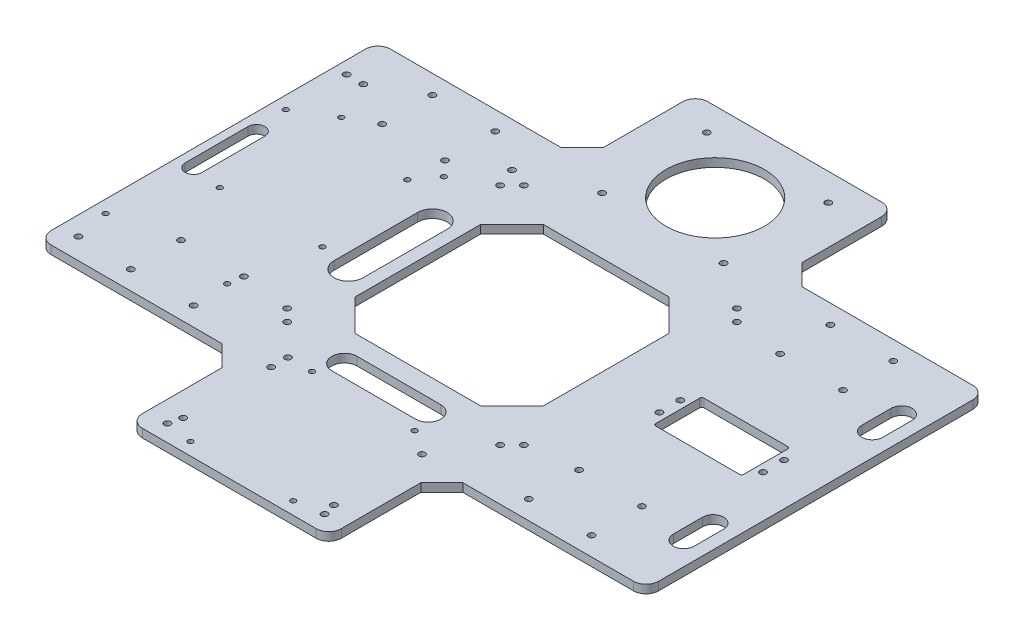
SolidWorks part; units mm, degrees
material "Thornel Mat VMA"
ref_plane "前视基准面" through (0, 0, 0) normal (0, 0, 1) x (1, 0, 0)
ref_plane "上视基准面" through (0, 0, 0) normal (0, 1, 0) x (1, 0, 0)
ref_plane "右视基准面" through (0, 0, 0) normal (1, 0, 0) x (0, 0, -1)
other "Configuration Table"
sketch "草图1" plane through (0, 0, 0) normal (0, 1, 0) x (1, 0, 0)
  line L0 (0, 0) -> (0, 135) construction
  line L1 (-145, -135) -> (145, -135)
  line L2 (-145, -135) -> (-145, 135)
  line L3 (-145, 135) -> (145, 135)
  line L4 (145, -135) -> (145, 135)
  line L5 (-145, -135) -> (145, 135) construction
  line L6 (-145, 135) -> (145, -135) construction
  line L7 (0, 0) -> (145, 0) construction
  line L8 (-47.5, 135) -> (-47.5, 81)
  line L9 (-47.5, 81) -> (-145, 81)
  line L10 (47.5, 81) -> (145, 81)
  line L11 (47.5, 135) -> (47.5, 81)
  line L12 (47.5, -81) -> (145, -81)
  line L13 (47.5, -135) -> (47.5, -81)
  line L14 (-47.5, -81) -> (-145, -81)
  line L15 (-47.5, -135) -> (-47.5, -81)
  point P0 (0, 0)
  dimension "D1" = 290
  dimension "D2" = 270
  dimension "D3" = 162
  dimension "D4" = 95
extrude "凸台-拉伸1" add sketch "草图1" along normal blind 4 contours L15 L1 L13 L12 L4 L10 L11 L3 L8 L9 L2 L14
sketch "草图2" plane through (0, 4, 0) normal (0, 1, 0) x (1, 0, 0)
  line L0 (0, 0) -> (145, 0) construction
  line L1 (145, -81) -> (145, 81) construction
  line L2 (0, 0) -> (0, 135) construction
  line L3 (-47.5, 135) -> (47.5, 135) construction
  line L4 (47.5, 81) -> (145, 81) construction
  circle A0 centre (110, 72) radius 1.5
  circle A1 centre (80, 72) radius 1.5
  circle A2 centre (80, 48) radius 1.5
  circle A3 centre (110, 48) radius 1.5
  circle A4 centre (110, -48) radius 1.5
  circle A5 centre (110, -72) radius 1.5
  circle A6 centre (80, -48) radius 1.5
  circle A7 centre (80, -72) radius 1.5
  circle A8 centre (-80, -72) radius 1.5
  circle A9 centre (-80, -48) radius 1.5
  circle A10 centre (-110, -72) radius 1.5
  circle A11 centre (-110, -48) radius 1.5
  circle A12 centre (-110, 48) radius 1.5
  circle A13 centre (-80, 48) radius 1.5
  circle A14 centre (-80, 72) radius 1.5
  circle A15 centre (-110, 72) radius 1.5
  dimension "D1" = 3
  dimension "D2" = 3
  dimension "D3" = 3
  dimension "D4" = 3
  dimension "D11" = 80
  dimension "D12" = 9
  dimension "D5" = 24
  dimension "D6" = 24
  dimension "D7" = 30
  dimension "D8" = 30
  dimension "D9" = 80
  dimension "D10" = 9
extrude "切除-拉伸1" cut sketch "草图2" against normal blind 4
sketch "草图3" plane through (0, 4, 0) normal (0, 1, 0) x (1, 0, 0)
  line L0 (0, 0) -> (0, 110.5115) construction
  line L1 (0, 0) -> (145, 0) construction
  line L2 (145, -81) -> (145, 81) construction
  line L3 (-86.4083, 97) -> (86.4083, 97) construction
  line L4 (0, 0) -> (0, 108.4938) construction
  line L7 (0, 0) -> (0, -114.288) construction
  circle A5 centre (0, 97) radius 23.5
  circle A33 centre (29, 122) radius 1.5
  circle A34 centre (29, 72) radius 1.5
  circle A35 centre (-29, 72) radius 1.5
  circle A36 centre (-29, 122) radius 1.5
  point P13 (0, 97)
  dimension "D2" = 97
  dimension "D6" = 47
  dimension "D12" = 25
  dimension "D8" = 3
  dimension "D5" = 0
  dimension "D9" = 29
extrude "切除-拉伸2" cut sketch "草图3" against normal blind 4
sketch "草图4" plane through (0, 4, 0) normal (0, 1, 0) x (1, 0, 0)
  line L1 (-45, -45) -> (45, -45)
  line L2 (-45, -45) -> (-45, 45)
  line L3 (-45, 45) -> (45, 45)
  line L4 (45, -45) -> (45, 45)
  line L5 (-45, -45) -> (45, 45) construction
  line L6 (-45, 45) -> (45, -45) construction
  point P0 (0, 0)
  dimension "D1" = 90
  dimension "D2" = 90
extrude "切除-拉伸3" cut sketch "草图4" against normal blind 4
fillet "圆角3" radius 6 8 edges at (-47.5, 2, -135) (47.5, 2, -135) (145, 2, -81) (145, 2, 81) (-47.5, 2, 135) (47.5, 2, 135) (-145, 2, 81) (-145, 2, -81)
chamfer "倒角1" distance 10 angle 45 4 edges at (47.5, 2, 81) (-47.5, 2, 81) (47.5, 2, -81) (-47.5, 2, -81)
sketch "草图7" plane through (0, 4, 0) normal (0, 1, 0) x (1, 0, 0)
  line L0 (0, 0) -> (0, 142.9478) construction
  line L1 (0, 0) -> (-184.5222, 0) construction
  line L2 (-137, -15) -> (-137, 15) construction
  line L5 (-58, -20) -> (-58, 20) construction
  line L6 (-65, -20) -> (-65, 20)
  line L7 (-51, -20) -> (-51, 20)
  line L8 (0, 0) -> (165.4514, 0) construction
  line L14 (-110, 0) -> (-110, 75.2826) construction
  line L15 (134, 38) -> (134, 52) construction
  line L33 (-141, -15) -> (-141, 15)
  line L34 (-133, -15) -> (-133, 15)
  line L35 (63, 0) -> (63, 55.2292) construction
  line L36 (0, -15) -> (172.3256, -15) construction
  line L38 (129, 38) -> (129, 52)
  line L39 (139, 38) -> (139, 52)
  line L40 (134, -38) -> (134, -52) construction
  line L41 (129, -38) -> (129, -52)
  line L42 (139, -38) -> (139, -52)
  arc A2 (-65, -20) -> (-51, -20) centre (-58, -20) ccw
  arc A3 (-51, 20) -> (-65, 20) centre (-58, 20) ccw
  arc A34 (-141, -15) -> (-133, -15) centre (-137, -15) ccw
  arc A35 (-133, 15) -> (-141, 15) centre (-137, 15) ccw
  arc A56 (129, 38) -> (139, 38) centre (134, 38) ccw
  arc A57 (139, 52) -> (129, 52) centre (134, 52) ccw
  arc A58 (129, -38) -> (139, -38) centre (134, -38) cw
  arc A59 (139, -52) -> (129, -52) centre (134, -52) cw
  point P6 (-137, 0)
  point P13 (-58, 0)
  point P21 (134, 45)
  point P37 (134, -45)
  dimension "D2" = 30
  dimension "D5" = 7
  dimension "D8" = 5
  dimension "D10" = 45
  dimension "D9" = 134
  dimension "D3" = 4
  dimension "D23" = 15
  dimension "D1" = 14
  dimension "D4" = 40
  dimension "D6" = 58
  dimension "D7" = 110
  dimension "D20" = 133
  dimension "D24" = 63
extrude "切除-拉伸6" cut sketch "草图7" against normal blind 4
chamfer "倒角2" distance 15 angle 45 4 edges at (45, 2, 45) (-45, 2, 45) (45, 2, -45) (-45, 2, -45)
sketch "草图8" plane through (0, 4, 0) normal (0, 1, 0) x (1, 0, 0)
  line L0 (0, 0) -> (0, 168.9929) construction
  line L1 (0, 0) -> (-169.1558, 0) construction
  line L2 (-103, 0) -> (-103, 65.828) construction
  line L3 (-103, -6) -> (-155.6162, -6) construction
  line L4 (0, 0) -> (-184.1789, 0) construction
  line L5 (0, 0) -> (0, 73.477) construction
  line L6 (-57.5, 81) -> (-139, 81) construction
  circle A15 centre (-139, 60) radius 1.5
  circle A16 centre (-131, 60) radius 1.5
  dimension "D2" = 8
  dimension "D4" = 103
  dimension "D5" = 6
  dimension "D6" = 0
  dimension "D7" = 3
  dimension "D8" = 3
  dimension "D11" = 28
  dimension "D12" = 36
  dimension "D10" = 21
extrude "切除-拉伸7" cut sketch "草图8" against normal blind 4
sketch "草图9" plane through (0, 4, 0) normal (0, 1, 0) x (1, 0, 0)
  line L0 (0, 0) -> (0, 165.3902) construction
  line L1 (0, 0) -> (179.4814, 0) construction
  line L2 (50.8431, 56.5) -> (56.5, 50.8431) construction
  line L3 (-62.5, -62.5) -> (62.5, -62.5) construction
  line L4 (-62.5, -62.5) -> (-62.5, 62.5) construction
  line L5 (-62.5, 62.5) -> (62.5, 62.5) construction
  line L6 (62.5, -62.5) -> (62.5, 62.5) construction
  line L7 (-62.5, -62.5) -> (62.5, 62.5) construction
  line L8 (-62.5, 62.5) -> (62.5, -62.5) construction
  line L18 (-50.3018, -50.3018) -> (40.4104, 40.4104) construction
  line L23 (-50.8431, -50.8431) -> (45.8431, 45.8431) construction
  line L24 (-48.3431, 48.3431) -> (48.3431, -48.3431) construction
  line L29 (-52.5221, -52.5221) -> (52.5221, 52.5221) construction
  line L30 (-52.5221, 52.5221) -> (52.5221, -52.5221) construction
  circle A0 centre (50.8431, 56.5) radius 1.5
  circle A1 centre (56.5, 50.8431) radius 1.5
  circle A2 centre (56.5, -50.8431) radius 1.5
  circle A3 centre (50.8431, -56.5) radius 1.5
  circle A4 centre (-50.8431, -56.5) radius 1.5
  circle A5 centre (-56.5, -50.8431) radius 1.5
  circle A6 centre (-56.5, 50.8431) radius 1.5
  circle A7 centre (-50.8431, 56.5) radius 1.5
  circle A8 centre (-37.5, -127) radius 1.5
  circle A9 centre (37.5, -127) radius 1.5
  dimension "D3" = 3
  dimension "D4" = 3
  dimension "D6" = 8
  dimension "D9" = 3
  dimension "D11" = 127
  dimension "D1" = 125
  dimension "D2" = 125
  dimension "D5" = 45
  dimension "D7" = 6
  dimension "D8" = 6
  dimension "D10" = 37.5
extrude "切除-拉伸8" cut sketch "草图9" against normal blind 4
sketch "草图10" plane through (0, 4, 0) normal (0, 1, 0) x (1, 0, 0)
  line L0 (0, 0) -> (173.0266, 0) construction
  line L1 (0, 0) -> (0, 114.2255) construction
sketch "草图11" plane through (0, 4, 0) normal (0, 1, 0) x (1, 0, 0)
  line L0 (0, 0) -> (183.5565, 0) construction
  line L1 (0, 0) -> (0, -155.5612) construction
sketch "草图12" plane through (0, 4, 0) normal (0, 1, 0) x (1, 0, 0)
  line L0 (-20, -60) -> (20, -60) construction
  line L1 (0, 0) -> (0, -155.5612) construction
  line L2 (-20, -54) -> (20, -54)
  line L3 (-20, -66) -> (20, -66)
  line L4 (0, 0) -> (173.0266, 0) construction
  arc A0 (-20, -54) -> (-20, -66) centre (-20, -60) ccw
  arc A1 (20, -66) -> (20, -54) centre (20, -60) ccw
  point P4 (0, -60)
  dimension "D2" = 6
  dimension "D1" = 40
  dimension "D3" = 60
extrude "切除-拉伸9" cut sketch "草图12" against normal blind 10
sketch "草图14" plane through (0, 4, 0) normal (0, 1, 0) x (1, 0, 0)
  line L0 (0, 0) -> (0, -145.4864) construction
  line L1 (0, 0) -> (173.1076, 0) construction
  line L2 (0, -100) -> (89.1596, -100) construction
  circle A0 centre (36, -79) radius 1.5
  circle A1 centre (36, -121) radius 1.5
  circle A2 centre (-36, -121) radius 1.5
  circle A3 centre (-36, -79) radius 1.5
  circle A4 centre (-24.5, -71) radius 1.25
  circle A5 centre (24.5, -71) radius 1.25
  circle A6 centre (24.5, -129) radius 1.25
  circle A7 centre (-24.5, -129) radius 1.25
  dimension "D1" = 3
  dimension "D2" = 42
  dimension "D3" = 72
  dimension "D5" = 2.5
  dimension "D6" = 49
  dimension "D7" = 58
  dimension "D4" = 100
extrude "切除-拉伸10" cut sketch "草图14" against normal blind 10
sketch "草图15" plane through (0, 4, 0) normal (0, 1, 0) x (1, 0, 0)
  line L0 (0, 0) -> (175.5609, 0) construction
  line L1 (0, 0) -> (0, 158.0719) construction
  line L2 (100.11, 0) -> (100.11, 39.6302) construction
  line L3 (79.11, -11.5) -> (121.11, -11.5)
  line L4 (79.11, -11.5) -> (79.11, 11.5)
  line L5 (79.11, 11.5) -> (121.11, 11.5)
  line L6 (121.11, -11.5) -> (121.11, 11.5)
  line L7 (79.11, -11.5) -> (121.11, 11.5) construction
  line L8 (79.11, 11.5) -> (121.11, -11.5) construction
  line L9 (110, 0) -> (110, 79.3701) construction
  circle A0 centre (75.36, 5) radius 1.5
  circle A2 centre (75.36, -5) radius 1.5
  circle A4 centre (124.86, -5) radius 1.5
  circle A5 centre (124.86, 5) radius 1.5
  point P3 (100.11, 0)
  dimension "D3" = 10
  dimension "D4" = 3
  dimension "D5" = 49.5
  dimension "D1" = 42
  dimension "D2" = 23
  dimension "D6" = 9.89
  dimension "D7" = 110
extrude "切除-拉伸11" cut sketch "草图15" against normal blind 10
fillet "圆角4" radius 1 4 edges at (79.11, 2, 11.5) (121.11, 2, 11.5) (121.11, 2, -11.5) (79.11, 2, -11.5)
sketch "草图16" plane through (0, 4, 0) normal (0, 1, 0) x (1, 0, 0)
  line L0 (0, 12) -> (-202.0071, 12) construction
  line L1 (0, 12) -> (0, 203.0309) construction
  line L2 (-98, -2.3134) -> (-98, 98.9217) construction
  line L4 (0, 0) -> (0, 12) construction
  line L5 (0, 0) -> (-183.682, 0) construction
  circle A0 centre (-73.5, 41) radius 1.25
  circle A1 centre (-122.5, 41) radius 1.25
  circle A2 centre (-73.5, -17) radius 1.25
  circle A3 centre (-122.5, -17) radius 1.25
  dimension "D1" = 58
  dimension "D2" = 49
  dimension "D3" = 2.5
  dimension "D4" = 98
  dimension "D5" = 12
extrude "切除-拉伸12" cut sketch "草图16" against normal blind 10
sketch "草图19" plane through (0, 4, 0) normal (0, 1, 0) x (1, 0, 0)
  line L0 (0, 0) -> (-178.7427, 0) construction
  line L1 (0, 0) -> (0, 171.7177) construction
  line L2 (-98, -10.9053) -> (-98, 46.7773) construction
  line L3 (-98, -7.4) -> (-15.7423, -7.4) construction
  circle A0 centre (-65, 50) radius 1.5
  circle A1 centre (-131, 50) radius 1.5
  circle A2 centre (-65, -64.8) radius 1.5
  circle A3 centre (-131, -64.8) radius 1.5
  dimension "D1" = 3
  dimension "D2" = 114.8
  dimension "D3" = 66
  dimension "D4" = 98
  dimension "D5" = 7.4
sketch "草图20" plane through (0, 4, 0) normal (0, 1, 0) x (1, 0, 0)
  line L0 (0, 0) -> (0, 140.7476) construction
  line L1 (0, 0) -> (-188.6657, 0) construction
  circle A0 centre (-60, 60) radius 1.5
  dimension "D1" = 3
  dimension "D2" = 60
  dimension "D3" = 60
sketch "草图22" plane through (0, 4, 0) normal (0, 1, 0) x (1, 0, 0)
  line L0 (0, 0) -> (154.1719, 0) construction
  line L1 (61, 0) -> (61, 40.4074) construction
  circle A0 centre (73, 13) radius 1.5
  circle A1 centre (49, 13) radius 1.5
  circle A2 centre (73, -13) radius 1.5
  circle A3 centre (49, -13) radius 1.5
  dimension "D1" = 24
  dimension "D2" = 26
  dimension "D3" = 3
  dimension "D4" = 61
sketch "草图23" plane through (0, 4, 0) normal (0, 1, 0) x (1, 0, 0)
  line L0 (0, 0) -> (-194.1261, 0) construction
  line L1 (-110, 0) -> (-110, 133.2192) construction
  line L3 (0, 0) -> (0, 84.0673) construction
  line L4 (0, -12) -> (-198.9065, -12) construction
  circle A0 centre (-81, 31) radius 1.25
  circle A3 centre (-139, 31) radius 1.25
  circle A4 centre (-81, -55) radius 1.25
  circle A5 centre (-139, -55) radius 1.25
  dimension "D1" = 2.5
  dimension "D2" = 58
  dimension "D3" = 86
  dimension "D5" = 12
  dimension "D4" = 110
extrude "切除-拉伸14" cut sketch "草图23" against normal blind 10
sketch "草图24" plane through (0, 4, 0) normal (0, 1, 0) x (1, 0, 0)
  line L0 (0, 0) -> (-236.5327, 0) construction
  line L1 (0, 0) -> (0, -171.9197) construction
  line L2 (0, -96) -> (-165.3693, -96) construction
  line L3 (-86, 0) -> (-86, -158.0192) construction
  circle A0 centre (-136, -71) radius 1.5
  circle A1 centre (-36, -71) radius 1.5
  circle A2 centre (-36, -121) radius 1.5
  dimension "D1" = 3
  dimension "D2" = 100
  dimension "D3" = 50
  dimension "D4" = 96
  dimension "D5" = 86
extrude "切除-拉伸15" cut sketch "草图24" against normal blind 10
extrude "切除-拉伸16" cut sketch "草图20" against normal blind 10
sketch "草图25" plane through (0, 4, 0) normal (0, 1, 0) x (1, 0, 0)
  line L0 (0, 0) -> (201.6978, 0) construction
  line L1 (0, 0) -> (0, 184.1709) construction
sketch "草图26" plane through (0, 0, 0) normal (1, 0, 0) x (0, 0, -1)
  line L0 (0, 0) -> (0, 117.1786) construction
